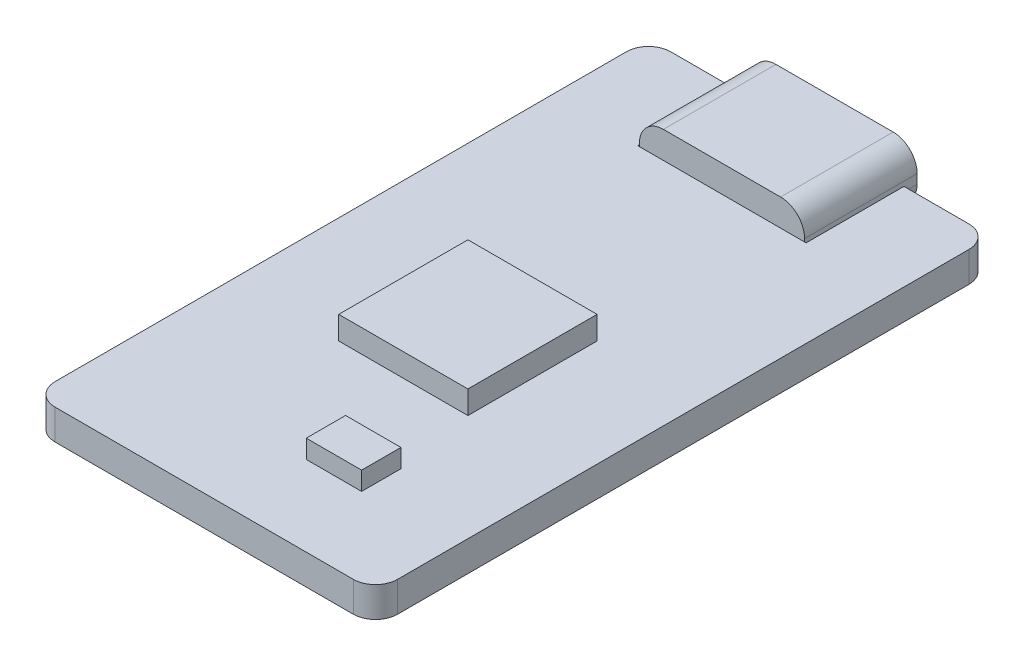
SolidWorks part; units mm, degrees
ref_plane "Front Plane" through (0, 0, 0) normal (0, 0, 1) x (1, 0, 0)
ref_plane "Top Plane" through (0, 0, 0) normal (0, 1, 0) x (1, 0, 0)
ref_plane "Right Plane" through (0, 0, 0) normal (1, 0, 0) x (0, 0, -1)
sketch "Sketch1" plane through (0, 0, 0) normal (0, 1, 0) x (1, 0, 0)
  line L1 (-9.28, 0) -> (9.28, 0)
  line L2 (-9.28, 0) -> (-9.28, -33.36)
  line L3 (-9.28, -33.36) -> (9.28, -33.36)
  line L4 (9.28, 0) -> (9.28, -33.36)
  point P4 (0, 0)
  dimension "D1" = 18.56
  dimension "D2" = 33.36
extrude "Boss-Extrude1" add sketch "Sketch1" along normal blind 1.64
fillet "Fillet1" radius 1.2 4 edges at (-9.28, 0.82, 0) (9.28, 0.82, 0) (9.28, 0.82, 33.36) (-9.28, 0.82, 33.36)
sketch "Sketch2" plane through (0, 1.64, 0) normal (0, 1, 0) x (1, 0, 0)
  line L0 (8.08, 0) -> (-8.08, 0) construction
  line L1 (-4.56, 0) -> (4.56, 0)
  line L2 (-4.56, 0) -> (-4.56, -5.3)
  line L3 (-4.56, -5.3) -> (4.56, -5.3)
  line L4 (4.56, 0) -> (4.56, -5.3)
  point P6 (0, -5.3)
  dimension "D1" = 5.3
  dimension "D2" = 9.12
extrude "Cut-Extrude1" cut sketch "Sketch2" against normal through all
sketch "Sketch3" plane through (0, 0, 5.3) normal (0, 0, -1) x (-1, 0, 0)
  line L0 (4.56, 0) -> (-4.56, 0) construction
  line L1 (-3.175, 0) -> (3.175, 0)
  line L2 (-4.475, 1.3) -> (-4.475, 1.8)
  line L3 (-3.175, 3.1) -> (3.175, 3.1)
  line L4 (4.475, 1.3) -> (4.475, 1.8)
  line L5 (8.08, 1.64) -> (-8.08, 1.64) construction
  arc A0 (3.175, 3.1) -> (4.475, 1.8) centre (3.175, 1.8) cw
  arc A1 (4.475, 1.3) -> (3.175, 0) centre (3.175, 1.3) cw
  arc A2 (-3.175, 0) -> (-4.475, 1.3) centre (-3.175, 1.3) cw
  arc A3 (-4.475, 1.8) -> (-3.175, 3.1) centre (-3.175, 1.8) cw
  point P12 (-4.475, 0)
  point P15 (0, 3.1)
  point P18 (0, 1.64)
  dimension "D1" = 1.3
  dimension "D2" = 3.1
  dimension "D3" = 8.95
extrude "Boss-Extrude2" add sketch "Sketch3" along normal blind 6.1
sketch "Sketch4" plane through (0, 0, -0.8) normal (0, 0, -1) x (-1, 0, 0)
  line L5 (-3.175, 1.8) -> (3.175, 1.8)
  line L6 (-3.175, 1.8) -> (-3.175, 1.3)
  line L7 (-3.175, 1.3) -> (3.175, 1.3)
  line L8 (3.175, 2.8) -> (-3.175, 2.8)
  line L9 (-4.175, 1.8) -> (-4.175, 1.3)
  line L10 (-3.175, 0.3) -> (3.175, 0.3)
  line L11 (4.175, 1.3) -> (4.175, 1.8)
  line L12 (3.175, 2.8) -> (-3.175, 2.8)
  line L13 (-4.175, 1.8) -> (-4.175, 1.3)
  line L14 (-3.175, 0.3) -> (3.175, 0.3)
  line L15 (4.175, 1.3) -> (4.175, 1.8)
  line L16 (3.175, 1.8) -> (3.175, 1.3)
  arc A8 (4.175, 1.8) -> (3.175, 2.8) centre (3.175, 1.8) ccw
  arc A9 (-3.175, 2.8) -> (-4.175, 1.8) centre (-3.175, 1.8) ccw
  arc A10 (-4.175, 1.3) -> (-3.175, 0.3) centre (-3.175, 1.3) ccw
  arc A11 (3.175, 0.3) -> (4.175, 1.3) centre (3.175, 1.3) ccw
  arc A12 (4.175, 1.8) -> (3.175, 2.8) centre (3.175, 1.8) ccw
  arc A13 (-3.175, 2.8) -> (-4.175, 1.8) centre (-3.175, 1.8) ccw
  arc A14 (-4.175, 1.3) -> (-3.175, 0.3) centre (-3.175, 1.3) ccw
  arc A15 (3.175, 0.3) -> (4.175, 1.3) centre (3.175, 1.3) ccw
  dimension "D1" = 0.3
extrude "Cut-Extrude2" cut sketch "Sketch4" against normal blind 5
sketch "Sketch5" plane through (0, 0, -0.8) normal (0, 0, -1) x (-1, 0, 0)
  line L4 (3.175, 1.3) -> (3.175, 1.8)
  line L5 (3.175, 1.8) -> (-3.175, 1.8)
  line L6 (-3.175, 1.8) -> (-3.175, 1.3)
  line L7 (-3.175, 1.3) -> (3.175, 1.3)
  line L8 (3.175, 1.3) -> (3.175, 1.8)
  line L9 (3.175, 1.8) -> (-3.175, 1.8)
  line L10 (-3.175, 1.8) -> (-3.175, 1.3)
  line L11 (-3.175, 1.3) -> (3.175, 1.3)
  dimension "D1" = 0
extrude "Cut-Extrude3" cut sketch "Sketch5" against normal blind 0.4
sketch "Sketch7" plane through (0, 1.64, 0) normal (0, 1, 0) x (1, 0, 0)
  line L0 (-8.08, -33.36) -> (8.08, -33.36) construction
  line L1 (-3.5, -15.57) -> (3.5, -15.57)
  line L2 (-3.5, -15.57) -> (-3.5, -22.57)
  line L3 (-3.5, -22.57) -> (3.5, -22.57)
  line L4 (3.5, -15.57) -> (3.5, -22.57)
  point P7 (0, -15.57)
  dimension "D1" = 7
  dimension "D2" = 17.79
extrude "Boss-Extrude3" add sketch "Sketch7" along normal blind 1.25
sketch "Sketch8" plane through (0, 1.64, 0) normal (0, 1, 0) x (1, 0, 0)
  line L0 (-8.08, -33.36) -> (8.08, -33.36) construction
  line L1 (1.18, -26.88) -> (4.18, -26.88)
  line L2 (1.18, -26.88) -> (1.18, -29.01)
  line L3 (1.18, -29.01) -> (4.18, -29.01)
  line L4 (4.18, -26.88) -> (4.18, -29.01)
  line L5 (9.28, -32.16) -> (9.28, -1.2) construction
  dimension "D1" = 3
  dimension "D2" = 2.13
  dimension "D3" = 4.35
  dimension "D4" = 5.1
extrude "Boss-Extrude4" add sketch "Sketch8" along normal blind 1
equation "\"e\"=10"
